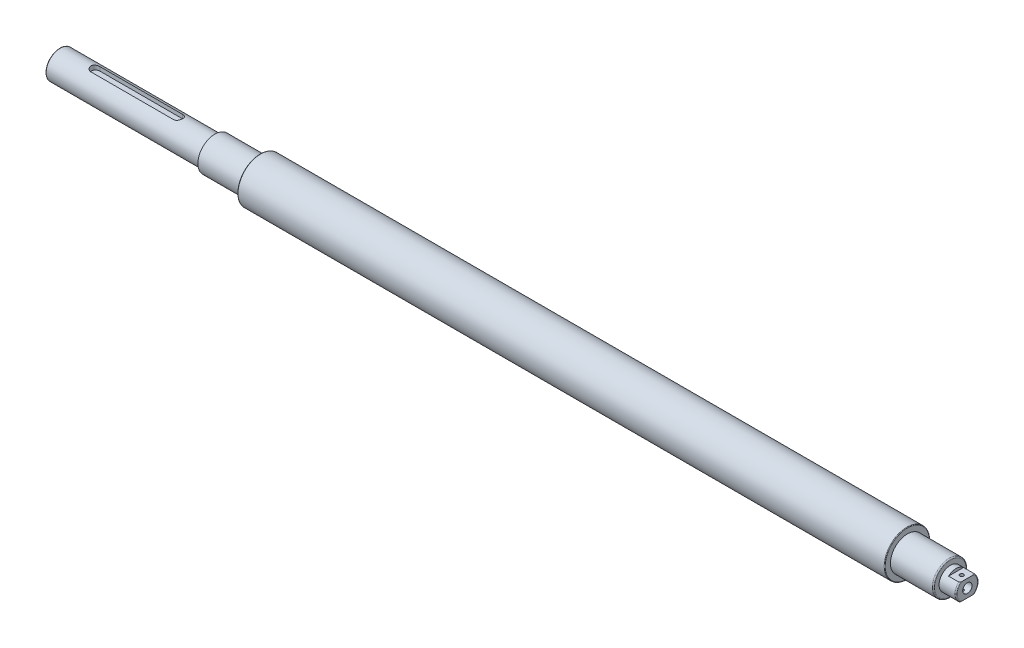
SolidWorks part; units mm, degrees
material "1.4003 (X2CrNi12)"
ref_plane "Ön Düzlem" through (0, 0, 0) normal (0, 0, 1) x (1, 0, 0)
ref_plane "Üst Düzlem" through (0, 0, 0) normal (0, 1, 0) x (1, 0, 0)
ref_plane "Sağ Düzlem" through (0, 0, 0) normal (1, 0, 0) x (0, 0, -1)
sketch "Çizim1" plane through (0, 0, 0) normal (0, 0, 1) x (1, 0, 0)
  line L0 (0, 0) -> (787, 0)
  line L1 (0, 0) -> (0, 12.5)
  line L2 (137, 15) -> (177, 15)
  line L3 (177, 15) -> (177, 20)
  line L4 (177, 20) -> (749, 20)
  line L5 (749, 20) -> (749, 15)
  line L6 (749, 15) -> (787, 15)
  line L7 (787, 15) -> (787, 0)
  line L8 (137, 15) -> (137, 12.5)
  line L9 (137, 12.5) -> (0, 12.5)
  point P3 (749, 17.5)
  dimension "D1" = 15
  dimension "D2" = 15
  dimension "D3" = 20
  dimension "D4" = 38
  dimension "D5" = 40
  dimension "D6" = 572
  dimension "D7" = 137
  dimension "D8" = 12.5
revolve "Döndür1" add sketch "Çizim1" angle 360 about L0
sketch "Çizim3" plane through (787, 0, 0) normal (1, 0, 0) x (0, 0, -1)
  circle A0 centre (0, 0) radius 10
  dimension "D1" = 20
extrude "Yükseklik-Ekstrüzyon2" add sketch "Çizim3" along normal blind 15
sketch "Çizim4" plane through (802, 0, 0) normal (1, 0, 0) x (0, 0, -1)
  circle A0 centre (0, 0) radius 4.1
  dimension "D1" = 8.2
extrude "Kes-Ekstrüzyon1" cut sketch "Çizim4" against normal blind 15
sketch "Çizim5" plane through (802, 0, 0) normal (1, 0, 0) x (0, 0, -1)
  line L1 (-7.5, 12.5) -> (7.5, 12.5)
  line L2 (-7.5, 12.5) -> (-7.5, 7.5)
  line L3 (-7.5, 7.5) -> (7.5, 7.5)
  line L4 (7.5, 12.5) -> (7.5, 7.5)
  line L5 (-7.5, 12.5) -> (7.5, 7.5) construction
  line L6 (-7.5, 7.5) -> (7.5, 12.5) construction
  line L7 (-7.5, -7.5) -> (7.5, -7.5)
  line L8 (-7.5, -7.5) -> (-7.5, -12.5)
  line L9 (-7.5, -12.5) -> (7.5, -12.5)
  line L10 (7.5, -7.5) -> (7.5, -12.5)
  line L11 (-7.5, -7.5) -> (7.5, -12.5) construction
  line L12 (-7.5, -12.5) -> (7.5, -7.5) construction
  circle A0 centre (0, 0) radius 10 construction
  circle A1 centre (0, 0) radius 10 construction
  point P0 (0, 10)
  point P11 (0, -10)
  dimension "D1" = 15
  dimension "D2" = 5
  dimension "D3" = 15
  dimension "D4" = 5
extrude "Kes-Ekstrüzyon2" cut sketch "Çizim5" against normal blind 10
sketch "Çizim6" plane through (0, 7.5, 0) normal (0, 1, 0) x (1, 0, 0)
  line L0 (802, -6.6144) -> (802, 6.6144) construction
  line L1 (802, -6.6144) -> (792, -6.6144) construction
  circle A0 centre (797, -0.0144) radius 1.65
  dimension "D1" = 3.3
  dimension "D2" = 5
  dimension "D3" = 6.6
extrude "Kes-Ekstrüzyon3" cut sketch "Çizim6" against normal blind 21
cosmetic thread "Kozmetik Diş Açma2" parameters "D2"=4
cosmetic thread "Kozmetik Diş Açma3" parameters "D2"=4
fillet "Radyus1" radius 1 3 edges at (802, 0, 10) (802, 0, -10) (787, -15, 0)
ref_plane "Düzlem1" through (0, 12.5, 0) normal (0, 1, 0) x (1, 0, 0)
sketch "Çizim7" plane through (0, 12.5, 0) normal (0, 1, 0) x (1, 0, 0)
  line L0 (31.5, 0) -> (104.5, 0) construction
  line L1 (31.5, 4) -> (104.5, 4)
  line L2 (31.5, -4) -> (104.5, -4)
  line L4 (0, 12.5) -> (0, -12.5) construction
  arc A0 (31.5, 4) -> (31.5, -4) centre (31.5, 0) ccw
  arc A1 (104.5, -4) -> (104.5, 4) centre (104.5, 0) ccw
  point P3 (68, 0)
  dimension "D1" = 4
  dimension "D2" = 73
  dimension "D4" = 68
extrude "Kes-Ekstrüzyon4" cut sketch "Çizim7" against normal blind 4.1
fillet "Radyus2" radius 0.5 3 edges at (0, -12.5, 0) (749, -20, 0) (177, -20, 0)
